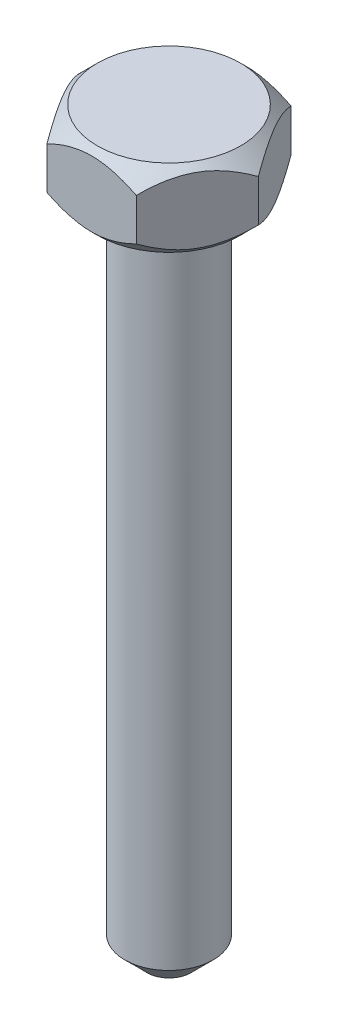
SolidWorks part; units mm, degrees
ref_plane "Спереди" through (0, 0, 0) normal (0, 0, 1) x (1, 0, 0)
ref_plane "Сверху" through (0, 0, 0) normal (0, 1, 0) x (1, 0, 0)
ref_plane "Справа" through (0, 0, 0) normal (1, 0, 0) x (0, 0, -1)
sketch "Эскиз1" plane through (0, 0, 0) normal (0, 1, 0) x (1, 0, 0)
  line L0 (-2.0207, 3.5) -> (2.0207, 3.5)
  line L1 (2.0207, 3.5) -> (4.0415, 0)
  line L2 (4.0415, 0) -> (2.0207, -3.5)
  line L3 (2.0207, -3.5) -> (-2.0207, -3.5)
  line L4 (-2.0207, -3.5) -> (-4.0415, 0)
  line L5 (-4.0415, 0) -> (-2.0207, 3.5)
  dimension "D5" = 3.5
  dimension "D2" = 120
  dimension "D3" = 120
  dimension "D4" = 120
  dimension "D6" = 3.5
  dimension "D7" = 3.5
  dimension "D8" = 3.5
  dimension "D9" = 3.5
  dimension "D10" = 120
  dimension "D11" = 3.5
extrude "Вытянуть1" add sketch "Эскиз1" against normal blind 3.5
sketch "Эскиз5" plane through (0, -3.5, 0) normal (0, -1, 0) x (1, 0, 0)
  circle A0 centre (0, 0) radius 2
  dimension "D1" = 4
extrude "Вытянуть2" add sketch "Эскиз5" along normal blind 30
chamfer "Фаска1" distance 1 angle 45 1 edges at (0, -33.5, -2)
ref_axis "Ось1" through (0, -3.5, 0) along (0, -1, 0)
ref_plane "Плоскость1" through (0, 0, 0) normal (0, 0, 1) x (1, 0, 0)
sketch "Эскиз4" plane through (0, 0, 0) normal (0, 0, 1) x (1, 0, 0)
  line L0 (-4.0415, -0.8) -> (-3.2415, 0)
  line L1 (-4.0415, -3.5) -> (-4.0415, 0) construction
  line L2 (-4.0415, 0) -> (-2.0207, 0) construction
  line L3 (-3.2415, 0) -> (-4.0415, 0)
  line L4 (-4.0415, 0) -> (-4.0415, -0.8)
  line L5 (-4.0415, -2.7) -> (-3.2415, -3.5)
  line L6 (-4.0415, -3.5) -> (-2.0207, -3.5) construction
  line L7 (-3.2415, -3.5) -> (-4.0415, -3.5)
  line L8 (-4.0415, -3.5) -> (-4.0415, -2.7)
  dimension "D1" = 0.8
  dimension "D2" = 0.8
  dimension "D3" = 0.8
  dimension "D4" = 0.8
revolve "Вырез-Повернуть1" cut sketch "Эскиз4" angle 360 about axis through (0, -3.5, 0) along (0, -1, 0)
